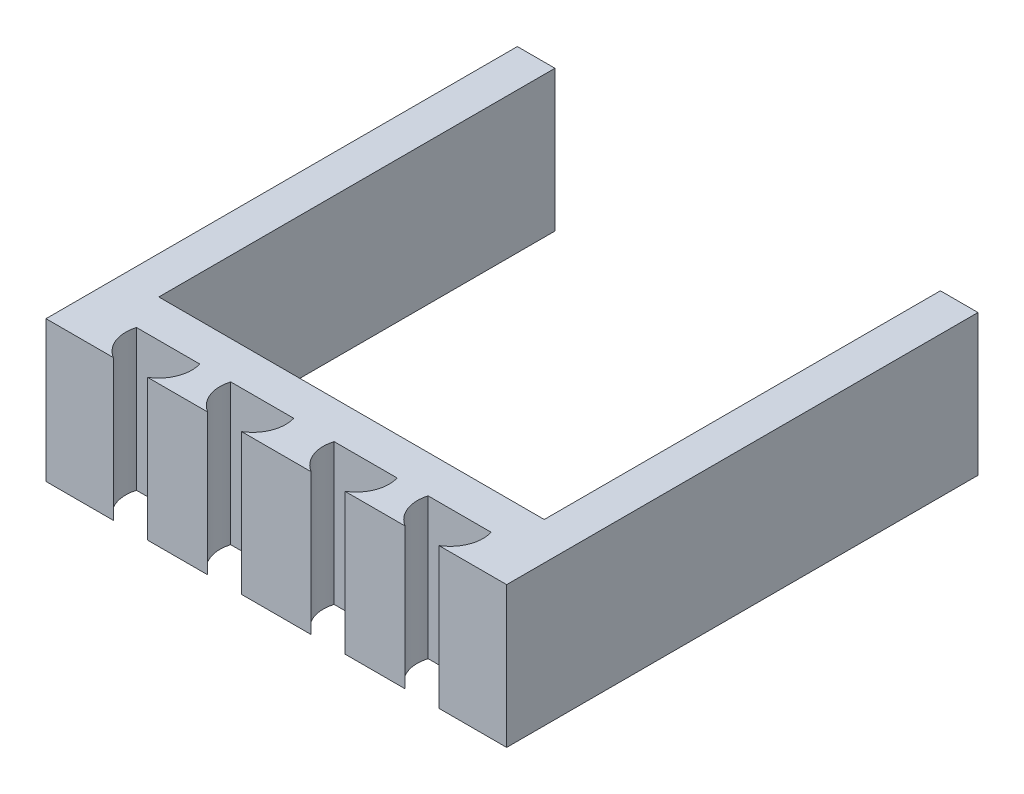
SolidWorks part; units mm, degrees
ref_plane "前视基准面" through (0, 0, 0) normal (0, 0, 1) x (1, 0, 0)
ref_plane "上视基准面" through (0, 0, 0) normal (0, 1, 0) x (1, 0, 0)
ref_plane "右视基准面" through (0, 0, 0) normal (1, 0, 0) x (0, 0, -1)
sketch "草图1" plane through (0, 0, 0) normal (0, 1, 0) x (1, 0, 0)
  line L0 (-20.6427, 18.0267) -> (-20.6427, -24.1102)
  line L1 (-20.6427, -24.1102) -> (20.3573, -24.1102)
  line L2 (20.3573, -24.1102) -> (20.3573, 18.0267)
  line L3 (20.3573, 18.0267) -> (24.3573, 18.0267)
  line L4 (24.3573, 18.0267) -> (24.3573, -28.1102)
  line L5 (24.3573, -28.1102) -> (-24.6427, -28.1102)
  line L6 (-24.6427, -28.1102) -> (-24.6427, 18.0267)
  line L7 (-24.6427, 18.0267) -> (-20.6427, 18.0267)
  dimension "D1" = 41
  dimension "D2" = 4
  dimension "D3" = 4
  dimension "D4" = 4
extrude "凸台-拉伸1" add sketch "草图1" along normal blind 15
sketch "草图3" plane through (0, 0, 0) normal (0, -1, 0) x (1, 0, 0)
  line L0 (-20.4961, 32.1102) -> (19.8779, 32.1102) construction
  line L1 (-24.6427, 28.1102) -> (24.3573, 28.1102) construction
  line L2 (-25.8165, 29.1102) -> (23.5262, 29.1102) construction
  line L3 (-24.6427, 28.1102) -> (-24.6427, 32.1102)
  line L4 (-24.6427, 32.1102) -> (-17.4863, 32.1102)
  line L5 (-20.6427, 24.1102) -> (-20.6427, -18.0267) construction
  line L6 (20.3573, -18.0267) -> (20.3573, 24.1102) construction
  line L7 (-19.0189, 28.1102) -> (-24.6427, 28.1102)
  line L8 (-13.8399, 32.1102) -> (-7.4455, 32.1102)
  line L9 (-12.2886, 28.1102) -> (-8.9968, 28.1102)
  line L10 (-3.8399, 32.1102) -> (3.5545, 32.1102)
  line L11 (-2.2886, 28.1102) -> (2.0032, 28.1102)
  line L12 (7.1601, 32.1102) -> (13.5545, 32.1102)
  line L13 (8.7089, 28.1019) -> (12.0032, 28.1102)
  line L14 (17.1601, 32.1102) -> (24.3573, 32.1102)
  line L15 (24.3573, 32.1102) -> (24.3573, 28.1102)
  line L16 (24.3573, 28.1102) -> (18.7114, 28.1102)
  circle A0 centre (-15.6427, 29.1102) radius 3.5 construction
  arc A1 (-17.4863, 32.1102) -> (-19.0189, 28.1102) centre (-15.6427, 29.1102) ccw
  arc A2 (-13.8399, 32.1102) -> (-12.2886, 28.1102) centre (-15.6427, 29.1102) cw
  circle A3 centre (-5.6427, 29.1102) radius 3.5 construction
  circle A4 centre (5.3573, 29.1102) radius 3.5 construction
  circle A5 centre (15.3573, 29.1102) radius 3.5 construction
  arc A6 (-8.9968, 28.1102) -> (-7.4455, 32.1102) centre (-5.6427, 29.1102) cw
  arc A7 (-3.8399, 32.1102) -> (-2.2886, 28.1102) centre (-5.6427, 29.1102) cw
  arc A8 (3.5545, 32.1102) -> (2.0032, 28.1102) centre (5.3573, 29.1102) ccw
  arc A9 (7.1601, 32.1102) -> (8.7089, 28.1019) centre (5.3573, 29.1102) cw
  arc A10 (12.0032, 28.1102) -> (13.5545, 32.1102) centre (15.3573, 29.1102) cw
  arc A11 (18.7114, 28.1102) -> (17.1601, 32.1102) centre (15.3573, 29.1102) ccw
  point P18 (-13.8399, 32.1102)
  point P19 (-7.4455, 32.1102)
  point P20 (-17.4863, 32.1102)
  point P21 (-3.8399, 32.1102)
  point P22 (3.5545, 32.1102)
  point P23 (7.1601, 32.1102)
  point P24 (13.5545, 32.1102)
  point P25 (17.1601, 32.1102)
  point P26 (12.0032, 28.1102)
  point P27 (18.7114, 28.1102)
  point P28 (8.7114, 28.1102)
  point P29 (2.0032, 28.1102)
  point P30 (-2.2886, 28.1102)
  point P31 (-8.9968, 28.1102)
  point P32 (-12.2886, 28.1102)
  point P33 (-18.9968, 28.1102)
  point P50 (0, 0)
  dimension "D3" = 5
  dimension "D1" = 4
  dimension "D2" = 1
  dimension "D4" = 5
  dimension "D5" = 10
  dimension "D6" = 10
extrude "凸台-拉伸4" add sketch "草图3" against normal blind 15
